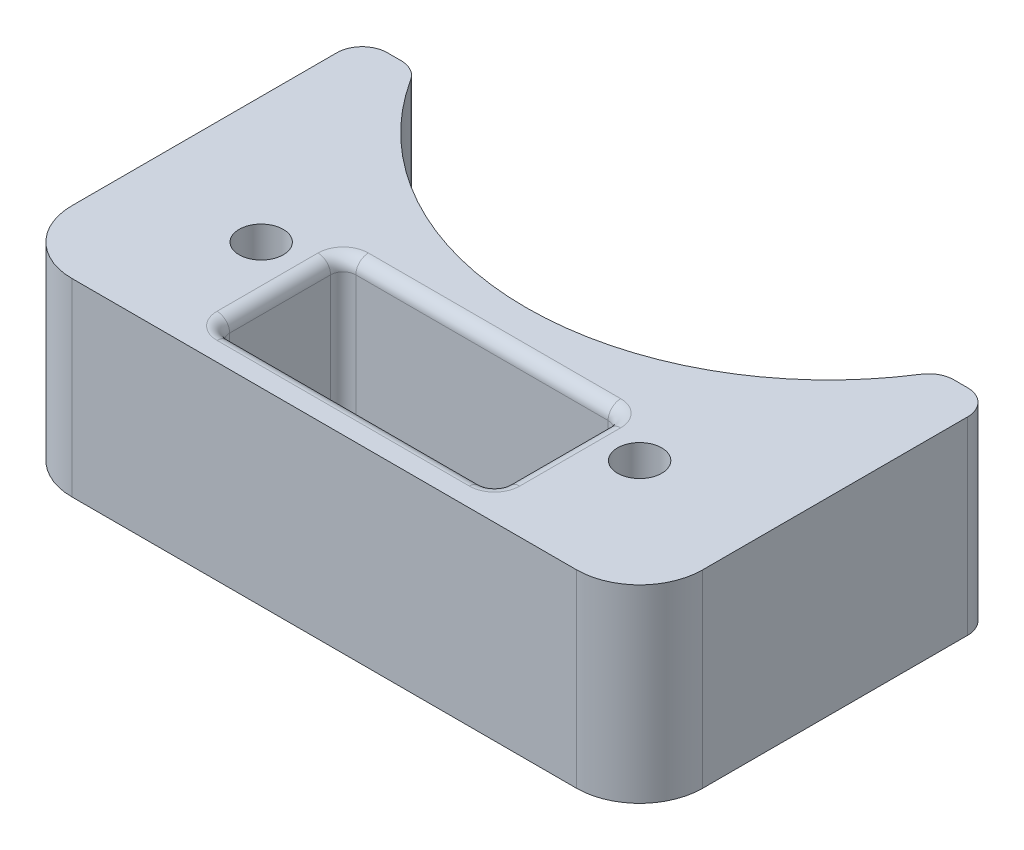
SolidWorks part; units mm, degrees
material "ABS"
ref_plane "前视基准面" through (0, 0, 0) normal (0, 0, 1) x (1, 0, 0)
ref_plane "上视基准面" through (0, 0, 0) normal (0, 1, 0) x (1, 0, 0)
ref_plane "右视基准面" through (0, 0, 0) normal (1, 0, 0) x (0, 0, -1)
other "Configuration Table"
sketch "草图1" plane through (0, 0, 0) normal (0, 1, 0) x (1, 0, 0)
  line L1 (-25, -25) -> (25, -25)
  line L2 (-25, -25) -> (-25, 25)
  line L3 (-25, 25) -> (25, 25)
  line L4 (25, -25) -> (25, 25)
  line L5 (-25, -25) -> (25, 25) construction
  line L6 (-25, 25) -> (25, -25) construction
  circle A0 centre (0, 0) radius 21.05
  dimension "D1" = 42.1
  dimension "D2" = 50
  dimension "D3" = 50
extrude "凸台-拉伸1" add sketch "草图1" along normal blind 15
sketch "草图2" plane through (0, 15, 0) normal (0, 1, 0) x (1, 0, 0)
  line L1 (-25, -40) -> (25, -40) construction
  line L2 (-25, -40) -> (-25, -55)
  line L3 (-25, -55) -> (25, -55)
  line L4 (25, -40) -> (25, -55)
  line L5 (-25, -47.5) -> (25, -47.5) construction
  line L6 (25, -25) -> (25, 25) construction
  line L7 (-25, -25) -> (25, -25)
  line L9 (-25, -40) -> (25, -40) construction
  line L11 (-25, -25) -> (25, -25)
  line L12 (-25, -25) -> (-25, -40)
  line L13 (-25, -40) -> (25, -40) construction
  line L14 (25, -25) -> (25, -40)
  circle A0 centre (-15, -47.5) radius 1.6
  circle A1 centre (15, -47.5) radius 1.6
  dimension "D2" = 3.2
  dimension "D3" = 3.2
  dimension "D4" = 10
  dimension "D1" = 15
  dimension "D5" = 10
  dimension "D6" = 40
extrude "凸台-拉伸2" add sketch "草图2" against normal up to surface (15 mm away)
fillet "圆角1" radius 3 4 edges at (25, 7.5, 55) (-25, 7.5, 55) (25, 7.5, -25) (-25, 7.5, -25)
sketch "草图3" plane through (0, 15, 0) normal (0, 1, 0) x (1, 0, 0)
  line L0 (0, 0) -> (0, -55) construction
  line L1 (-22, -55) -> (22, -55) construction
  line L2 (-15, -30) -> (15, -30) construction
  circle A0 centre (-15, -30) radius 1.75
  circle A1 centre (15, -30) radius 1.75
  dimension "D4" = 3.5
  dimension "D5" = 3.5
  dimension "D1" = 15
  dimension "D2" = 15
  dimension "D3" = 25
extrude "切除-拉伸1" cut sketch "草图3" against normal through all
sketch "草图4" plane through (0, 15, 0) normal (0, 1, 0) x (1, 0, 0)
  line L0 (-22, -55) -> (22, -55) construction
  line L1 (-31.3912, -40) -> (34.177, -40)
  line L2 (-31.3912, -40) -> (-31.3912, -60.4518)
  line L3 (-31.3912, -60.4518) -> (34.177, -60.4518)
  line L4 (34.177, -40) -> (34.177, -60.4518)
  line L11 (-32.2425, -12) -> (34.8543, -12)
  line L12 (-32.2425, -12) -> (-32.2425, 31.3532)
  line L13 (-32.2425, 31.3532) -> (34.8543, 31.3532)
  line L14 (34.8543, -12) -> (34.8543, 31.3532)
  circle A0 centre (0, 0) radius 24
  line M5 (-22, -55) -> (22, -55)
  arc M6 (22, -55) -> (25, -52) centre (22, -52) ccw
  line M7 (25, -52) -> (25, 22)
  arc M8 (25, 22) -> (22, 25) centre (22, 22) ccw
  line M9 (22, 25) -> (-22, 25)
  arc M10 (-22, 25) -> (-25, 22) centre (-22, 22) ccw
  line M11 (-25, 22) -> (-25, -52)
  arc M12 (-25, -52) -> (-22, -55) centre (-22, -52) ccw
  circle M13 centre (0, 0) radius 21.05
  circle M14 centre (15, -47.5) radius 1.6
  circle M15 centre (-15, -47.5) radius 1.6
  dimension "D2" = 48
  dimension "D1" = 15
  dimension "D3" = 28
extrude "切除-拉伸2" cut sketch "草图4" against normal through all contours L1 M11 M12 M5 M6 M7 M15 M14 | A0 L11 M7 M8 M9 M10 M11 | L11 A0 M13 | L11 A0 M13
fillet "圆角2" radius 2 4 edges at (-25, 7.5, 12) (20.7846, 7.5, 12) (-20.7846, 7.5, 12) (25, 7.5, 12)
fillet "圆角3" radius 5 2 edges at (-25, 7.5, 40) (25, 7.5, 40)
sketch "草图5" plane through (0, 15, 0) normal (0, 1, 0) x (1, 0, 0)
  line L0 (0, 0) -> (0, -32.5) construction
  line L2 (-20, -40) -> (20, -40) construction
  line L4 (-11, -37.5) -> (11, -37.5)
  line L5 (-11, -37.5) -> (-11, -27.5)
  line L6 (-11, -27.5) -> (11, -27.5)
  line L7 (11, -37.5) -> (11, -27.5)
  line L8 (-11, -37.5) -> (11, -27.5) construction
  line L9 (-11, -27.5) -> (11, -37.5) construction
  dimension "D1" = 7.5
  dimension "D2" = 10
  dimension "D3" = 22
extrude "切除-拉伸3" cut sketch "草图5" against normal through all
fillet "圆角4" radius 1 12 edges at (0, 0, 27.5) (0, 15, 27.5) (0, 0, 37.5) (0, 15, 37.5) (11, 7.5, 37.5) (11, 0, 32.5) (11, 7.5, 27.5) (11, 15, 32.5) (-11, 7.5, 27.5) (-11, 0, 32.5) (-11, 7.5, 37.5) (-11, 15, 32.5)
